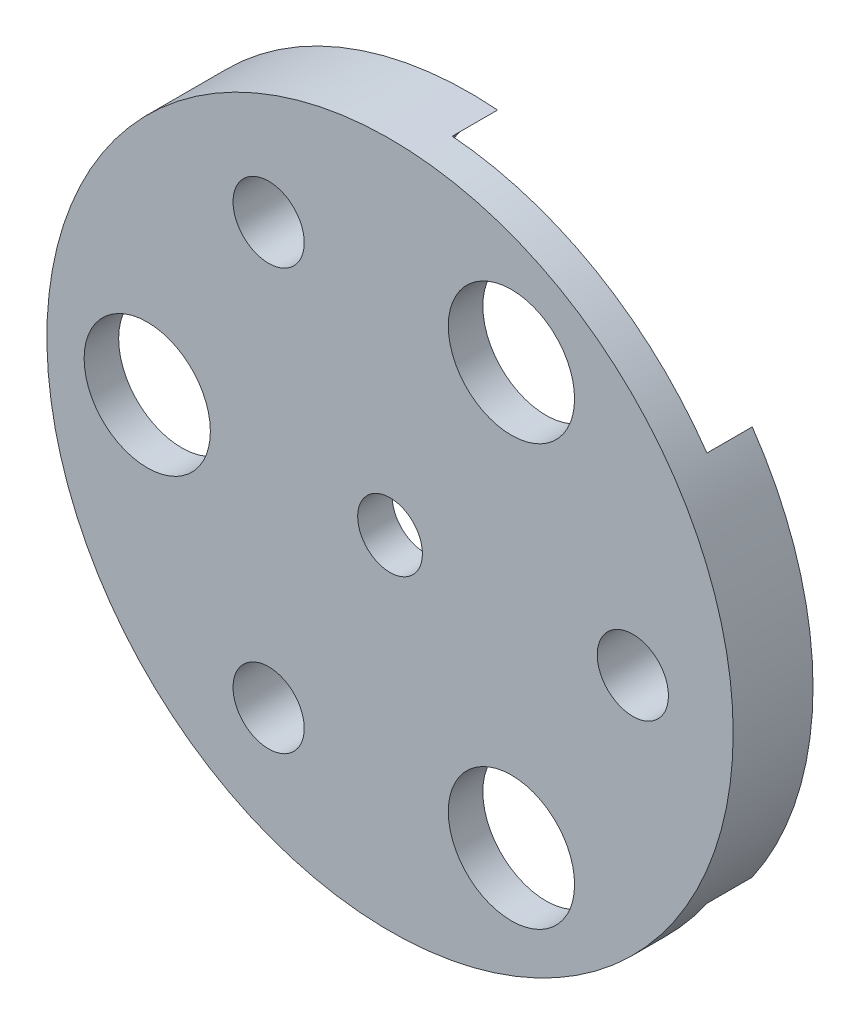
SolidWorks part; units mm, degrees
ref_plane "Front Plane" through (0, 0, 0) normal (0, 0, 1) x (1, 0, 0)
ref_plane "Top Plane" through (0, 0, 0) normal (0, 1, 0) x (1, 0, 0)
ref_plane "Right Plane" through (0, 0, 0) normal (1, 0, 0) x (0, 0, -1)
other "Graphic1"
other "Graphic (Closed) -1"
sketch "Sketch1" plane through (0, 0, 0) normal (0, 0, 1) x (1, 0, 0)
  line L0 (158.5699, 173.6177) -> (181.0699, 173.6177) construction
  circle A0 centre (169.8199, 173.6177) radius 15.9
  circle A1 centre (169.8199, 173.6177) radius 11.25 construction
  circle A2 centre (181.0699, 173.6177) radius 1.65
  circle A3 centre (158.5699, 173.6177) radius 2.925
  circle A4 centre (164.1949, 163.8749) radius 1.65
  circle A5 centre (164.1949, 183.3604) radius 1.65
  circle A6 centre (175.4449, 183.3604) radius 2.925
  circle A7 centre (175.4449, 163.8749) radius 2.925
  circle A8 centre (169.8199, 173.6177) radius 1.5
  point P15 (169.8199, 173.6177)
  point P20 (169.8199, 173.6177)
  dimension "D1" = 31.8
  dimension "D4" = 22.5
  dimension "D5" = 5.85
  dimension "D6" = 3.3
  dimension "D7" = 3
  dimension "D9" = 3
  dimension "D2" = 169.8199
  dimension "D3" = 173.6177
  dimension "D8" = 3
extrude "Boss-Extrude1" add sketch "Sketch1" along normal blind 3.7
sketch "Sketch2" plane through (0, 0, 0) normal (0, 0, -1) x (-1, 0, 0)
  circle A0 centre (-158.5699, 173.6177) radius 2.925 construction
  circle A1 centre (-181.0699, 173.6177) radius 1.65 construction
  circle A2 centre (-169.8199, 173.6177) radius 15.9 construction
  circle A3 centre (-158.5699, 173.6177) radius 2.925 construction
  circle A4 centre (-181.0699, 173.6177) radius 1.65 construction
  circle A5 centre (-169.8199, 173.6177) radius 15.9 construction
  circle A6 centre (-169.8199, 173.6177) radius 7.3472
  circle A7 centre (-158.5699, 173.6177) radius 7.492
  circle A8 centre (-175.4449, 163.8749) radius 7.492
  circle A9 centre (-175.4449, 183.3604) radius 7.492
  point P19 (-169.8199, 173.6177)
  circle M5 centre (-169.8199, 173.6177) radius 15.9
  circle M7 centre (-158.5699, 173.6177) radius 2.925
  circle M10 centre (-175.4449, 183.3604) radius 2.925
  circle M11 centre (-175.4449, 163.8749) radius 2.925
  dimension "D1" = 3
extrude "Cut-Extrude1" cut sketch "Sketch2" against normal blind 2.1 contours A7 A6 M5 M7 | A6 A7 | A9 A6 A8 A7 | A6 A9 | A6 A8 | A6 A8 M5 M11 | A9 A6 M5 M10
